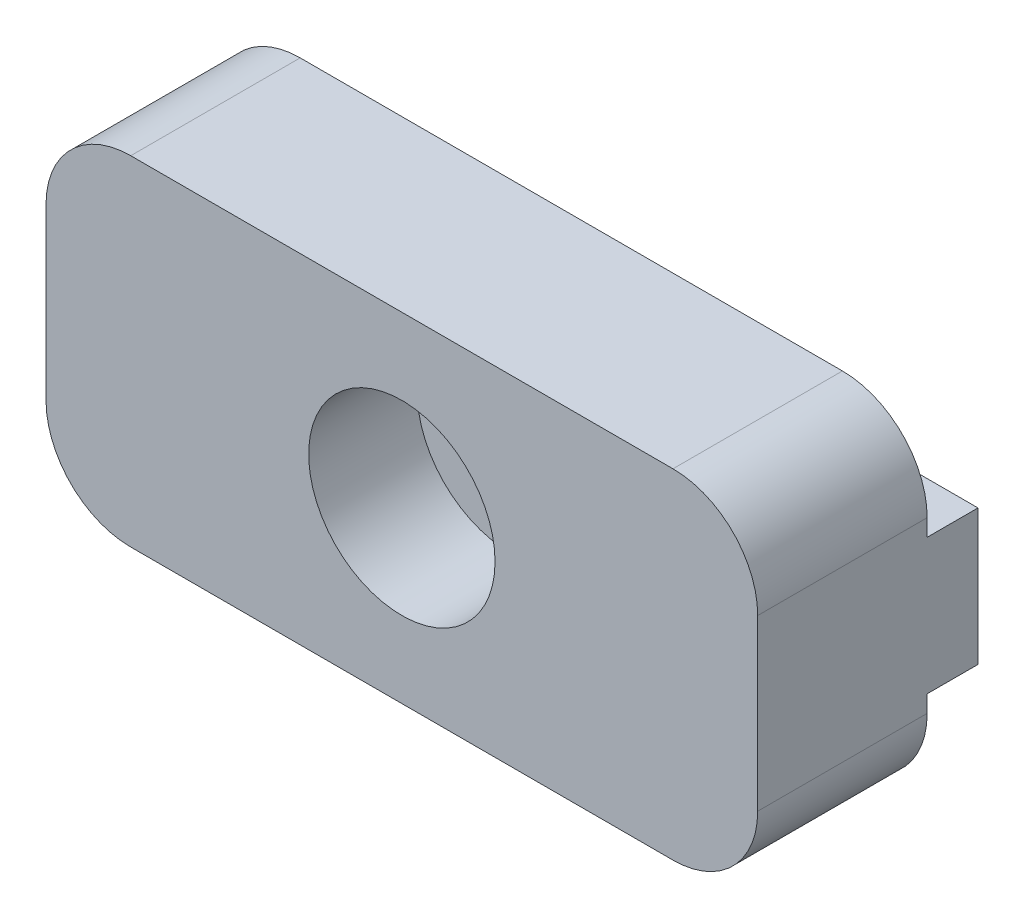
SolidWorks part; units mm, degrees
ref_plane "Přední rovina" through (0, 0, 0) normal (0, 0, 1) x (1, 0, 0)
ref_plane "Horní rovina" through (0, 0, 0) normal (0, 1, 0) x (1, 0, 0)
ref_plane "Pravá rovina" through (0, 0, 0) normal (1, 0, 0) x (0, 0, -1)
sketch "Base sketch" plane through (0, 0, 0) normal (0, 0, 1) x (1, 0, 0)
  line L1 (-21, 10) -> (21, 10)
  line L2 (-21, 10) -> (-21, -10)
  line L3 (-21, -10) -> (21, -10)
  line L4 (21, 10) -> (21, -10)
  line L5 (-21, 10) -> (21, -10) construction
  line L6 (-21, -10) -> (21, 10) construction
  point P0 (0, 0)
  dimension "D1" = 20
  dimension "D2" = 42
extrude "Base" add sketch "Base sketch" along normal blind 10
sketch "Mount screw sketch" plane through (0, 0, 10) normal (0, 0, 1) x (1, 0, 0)
  point P0 (0, 0)
hole_wizard "Mount screw" positions "Skica3" profile "Skica4" counterbore size "M6" standard "ISO" end condition up to next
sketch "Skica3" plane through (0, 0, 10) normal (0, 0, 1) x (1, 0, 0)
  point P0 (0, 0)
sketch "Skica4" plane through (0, 0, 10) normal (1, 0, 0) x (0, -1, 0)
  line L0 (0, 0) -> (0, 10)
  line L1 (0, 10) -> (3.3, 10)
  line L3 (3.3, 10) -> (3.3, 6.4)
  line L4 (3.3, 6.4) -> (5.5, 6.4)
  line L5 (5.5, 6.4) -> (5.5, 0)
  line L7 (5.5, 0) -> (0, 0)
  line L11 (0, -6.35) -> (0, 107.95) construction
  dimension "Průměr díry skrz" = 6.6
  dimension "Hloubka díry skrz" = 10
  dimension "Průměr válcového zahloubení" = 11
  dimension "Hloubka válcového zahloubení" = 6.4
sketch "Profile clip sketch" plane through (0, 0, 0) normal (0, 0, -1) x (-1, 0, 0)
  line L0 (21, 10) -> (21, -10) construction
  line L1 (-21, 4) -> (21, 4)
  line L2 (-21, 4) -> (-21, -4)
  line L3 (-21, -4) -> (21, -4)
  line L4 (21, 4) -> (21, -4)
  line L5 (-21, 4) -> (21, -4) construction
  line L6 (-21, -4) -> (21, 4) construction
  circle A0 centre (0, 0) radius 9
  point P0 (0, 0)
  line M3 (-21, 10) -> (-21, -10)
  line M5 (21, -10) -> (21, 10)
  dimension "D2" = 18
  dimension "D1" = 8
extrude "Profile clip" add sketch "Profile clip sketch" along normal blind 3 contours A0 L1 L3 M3 | A0 L3 L1 M5
fillet "Zaoblit1" radius 5 4 edges at (-21, 10, 5) (-21, -10, 5) (21, 10, 5) (21, -10, 5)
